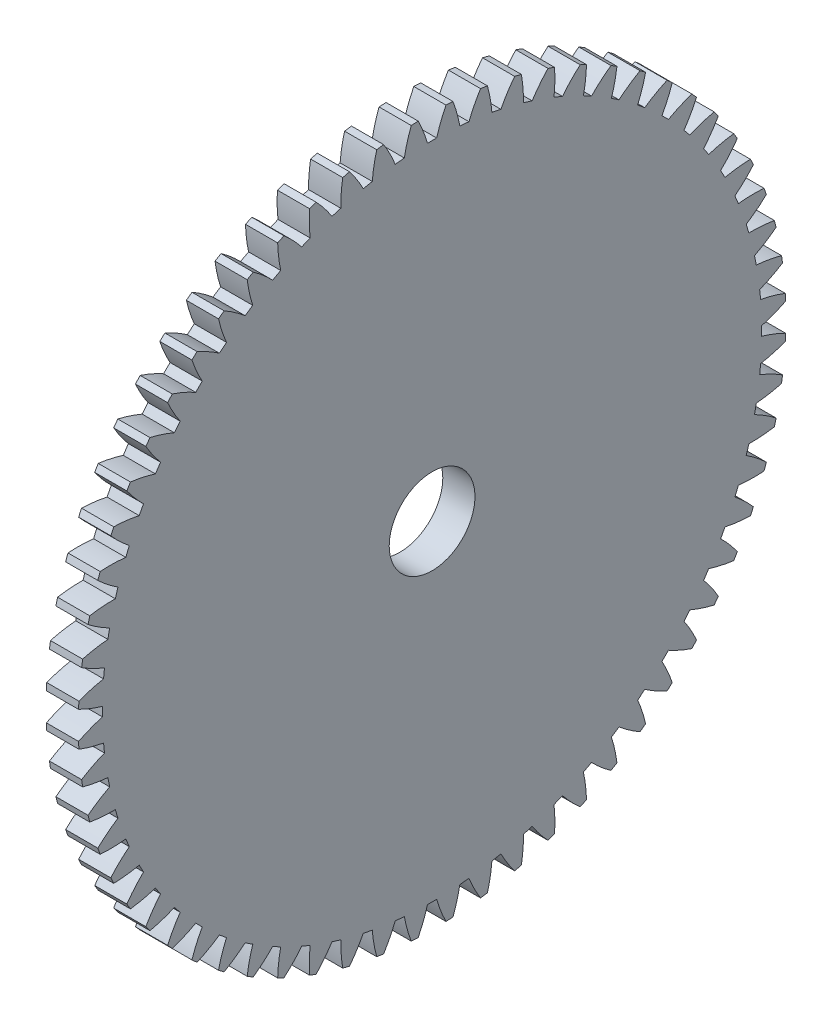
SolidWorks part; units mm, degrees
ref_plane "Plane1" through (0, 0, 0) normal (0, 0, 1) x (1, 0, 0)
ref_plane "Plane2" through (0, 0, 0) normal (0, 1, 0) x (1, 0, 0)
ref_plane "Plane3" through (0, 0, 0) normal (1, 0, 0) x (0, 0, -1)
sketch "HoldingSke" plane through (0, 0, 0) normal (0, 1, 0) x (1, 0, 0)
  line L0 (0, 0) -> (0.4384, -0.8988)
  line L1 (-15, 0) -> (100, 0) construction
  line L2 (0, 0) -> (-2.1039, 2.3779)
  line L3 (0, 0) -> (-11.863, 4.5341)
  line L4 (0, 0) -> (3.7858, 7.762)
  line L5 (0, 0) -> (-46.8476, -17.4728)
  line L6 (0, 0) -> (-2.4869, -1.6779)
  line L7 (-2.1039, 2.3779) -> (8.6586, 51.2059)
  line L8 (-76.2, 54.61) -> (-74.8, 54.61)
  line L9 (-71.009, 38.7566) -> (-53.1078, 45.2721)
  line L10 (-76.2, 71.12) -> (104.1128, 71.12)
  line L11 (0, 0) -> (-3, 0)
  line L12 (-76.2, 101.6) -> (-76.162, 101.6)
  line L13 (24.9733, 27.94) -> (52.9518, 28.4284)
  line L14 (24.9733, 27.94) -> (24.9743, 27.94)
  line L15 (24.9733, 27.94) -> (100.4006, 29.5858)
  line L16 (-63.627, -1) -> (-12.827, -1)
  circle A0 centre (0, 0) radius 4
  circle A1 centre (0, 0) radius 30.749
  circle A2 centre (0, 0) radius 37.5
  circle A3 centre (0, 0) radius 4
  dimension "MHD" = 61.498
  dimension "Hub_dia" = 75
  dimension "Bore" = 8
  dimension "MBD" = 8
  dimension "Num_teeth" = 64
  dimension "Pitch_radius" = 180.3128
  dimension "Pitch" = 1
  dimension "Width" = 3
  dimension "Overall_len" = 50
  dimension "Show_teeth" = 64
  dimension "Thickness" = 3
  dimension "OAL" = 50.0001
  dimension "T_dim" = 1.4
  dimension "Ap" = 20
  dimension "H" = 19.05
  dimension "Backlash" = 0.038
  dimension "Addendum_fac" = 1
  dimension "Dedendum_fac" = 1.25
  dimension "Clearance_fac" = 0.25
  dimension "Dedendum_add" = 0.001
  dimension "Module" = 1
sketch "BasProSke" plane through (0, 0, 0) normal (0, 1, 0) x (1, 0, 0)
  line L0 (-10, 0) -> (60, 0) construction
  line L1 (0, 0) -> (0, 33)
  line L2 (0, 0) -> (3, 0)
  line L3 (3, 0) -> (3, 33)
  line L4 (3, 33) -> (0, 33)
  dimension "Diameter" = 66
  dimension "Thickness" = 3
revolve "Base-Revolve" add sketch "BasProSke" angle 360 about L0
sketch "TooCutSke" plane through (0, 0, 0) normal (1, 0, 0) x (0, 0, -1)
  line L1 (0, 0) -> (0, 107) construction
  line L2 (0, 0) -> (-0.8518, 31.9887) construction
  line L3 (0, 0) -> (-3.1395, 63.9068) construction
  line L4 (-0.8518, 31.9887) -> (-1.5698, 31.9534) construction
  arc A0 (0.4278, 30.746) -> (-0.4278, 30.746) centre (0, 0) ccw
  arc A1 (1.3075, 32.9995) -> (-1.3075, 32.9995) centre (0, 0) ccw
  circle A2 centre (0, 0) radius 32 construction
  circle A3 centre (0, 0) radius 30.0702 construction
  arc A4 (-0.4278, 30.746) -> (-1.3075, 32.9995) centre (-12.7379, 27.2389) ccw
  arc A5 (1.3075, 32.9995) -> (0.4278, 30.746) centre (12.7379, 27.2389) ccw
  dimension "Root_dia" = 61.498
  dimension "Overcut_dia" = 66.0508
  dimension "Pitch_dia" = 64
  dimension "Base_dia" = 60.1403
  dimension "Flank_rad" = 12.8
  dimension "Half_ang" = 2.813
  dimension "Half_CT" = 0.7188
extrude "ToothCut" cut sketch "TooCutSke" along normal through all
fillet "Breaks" [suppressed] radius 0.02
fillet "RootFillets" [suppressed] radius 0.251
pattern_circular "TeethCuts" count 64 over 360 about axis through (0, 0, 0) along (1, 0, 0) of "ToothCut", "RootFillets", "Breaks"
sketch "HubNeaOneSke" plane through (0, 0, 0) normal (-1, 0, 0) x (0, 0, 1)
  circle A0 centre (0, 0) radius 30.749
  dimension "Diameter" = 61.498
extrude "HubNearOne" [suppressed] add sketch "HubNeaOneSke" along normal blind 47.0001
sketch "HubNeaBotSke" plane through (0, 0, 0) normal (-1, 0, 0) x (0, 0, 1)
  circle A0 centre (0, 0) radius 30.749
  dimension "Diameter" = 61.498
extrude "HubNearBoth" [suppressed] add sketch "HubNeaBotSke" along normal blind 23.5
ref_plane "FarPln" through (3, 0, 0) normal (1, 0, 0) x (0, 0, -1)
sketch "HubFarSke" plane through (3, 0, 0) normal (1, 0, 0) x (0, 0, -1)
  circle A0 centre (0, 0) radius 30.749
  dimension "Diameter" = 61.498
extrude "HubFar" [suppressed] add sketch "HubFarSke" along normal blind 23.5
sketch "BorSke" plane through (0, 0, 0) normal (1, 0, 0) x (0, 0, -1)
  circle A0 centre (0, 0) radius 4
  dimension "Diameter" = 8
extrude "Bore" cut sketch "BorSke" along normal mid plane 100.0001
sketch "KeySke" plane through (0, 0, 0) normal (1, 0, 0) x (0, 0, -1)
  line L0 (-1.5, 0) -> (-1.5, 5.4)
  line L1 (-1.5, 5.4) -> (1.5, 5.4)
  line L2 (1.5, 5.4) -> (1.5, 0)
  line L3 (0, 0) -> (0, 34) construction
  line L4 (-1.5, 0) -> (1.5, 0)
  dimension "Offset" = 5.4
  dimension "Width" = 3
extrude "Keyway" [suppressed] cut sketch "KeySke" along normal mid plane 100.0001
pattern_circular "Keyway2" [suppressed] count 2 every 90 about axis through (-10, 0, 0) along (1, 0, 0)
equation "' \"Module@HoldingSke\" = 6.35"
equation "' \"Num_teeth@HoldingSke\" = 12"
equation "' \"Ap@HoldingSke\" =  20"
equation "' \"Width@HoldingSke\" = 0.5 * 25.4"
equation "' \"Hub_dia@HoldingSke\"= 1 * 25.4"
equation "' \"Overall_len@HoldingSke\" = 1.0 * 25.4"
equation "' \"Bore@HoldingSke\" = 0.75 * 25.4"
equation "' \"T_dim@HoldingSke\" = 0.1 * 25.4"
equation "' \"Width@KeySke\" = 0.25 * 25.4"
equation "' \"Show_teeth@HoldingSke\" = 13"
equation "' \"Backlash@HoldingSke\" = 0.009 * 25.4"
equation "' \"Addendum_fac@HoldingSke\" = 1.0"
equation "' \"Dedendum_fac@HoldingSke\" = 1.25"
equation "' \"Dedendum_add@HoldingSke\" = 0.00005 * 25.4"
equation "' \"Clearance_fac@HoldingSke\" = 0.25"
equation "\"Pitch@HoldingSke\" = 1 / \"Module@HoldingSke\""
equation "\"Overcut_dia@TooCutSke\" = (\"Num_teeth@HoldingSke\" + 2 * \"Addendum_fac@HoldingSke\") / \"Pitch@HoldingSke\" + 0.002 * 25.4"
equation "\"Pitch_dia@TooCutSke\" = \"Num_teeth@HoldingSke\" / \"Pitch@HoldingSke\""
equation "\"Base_dia@TooCutSke\" = \"Num_teeth@HoldingSke\" / \"Pitch@HoldingSke\" * cos((\"Ap@HoldingSke\"  * 3.14159265 / 180))"
equation "\"Root_dia@TooCutSke\" = (\"Num_teeth@HoldingSke\" + 2) / \"Pitch@HoldingSke\" - 2 * (\"Addendum_fac@HoldingSke\" + \"Dedendum_fac@HoldingSke\") / \"Pitch@HoldingSke\" - \"Dedendum_add@HoldingSke\" * 2"
equation "\"Half_ang@TooCutSke\" = 180 / \"Num_teeth@HoldingSke\""
equation "\"Half_CT@TooCutSke\" = \"Num_teeth@HoldingSke\" / \"Pitch@HoldingSke\" * sin((3.14159265 / 2 / \"Num_teeth@HoldingSke\")) / 2 - 7 * \"Backlash@HoldingSke\" / 4"
equation "\"Flank_rad@TooCutSke\" = \"Num_teeth@HoldingSke\" / \"Pitch@HoldingSke\" / 5"
equation "\"Radius@RootFillets\" = \"Clearance_fac@HoldingSke\" / \"Pitch@HoldingSke\" + \"Dedendum_add@HoldingSke\""
equation "\"Break_rad@Breaks\" = 0.02 / \"Pitch@HoldingSke\""
equation "\"Thickness@HoldingSke\" = \"Width@HoldingSke\""
equation "\"OAL@HoldingSke\" = \"Thickness@HoldingSke\""
equation "\"MHD@HoldingSke\" = (\"Num_teeth@HoldingSke\" + 2) / \"Pitch@HoldingSke\" - 2 * (\"Addendum_fac@HoldingSke\" + \"Dedendum_fac@HoldingSke\")  / \"Pitch@HoldingSke\" - \"Dedendum_add@HoldingSke\" * 2"
equation "\"MBD@HoldingSke\" = (\"Num_teeth@HoldingSke\" + 2) / \"Pitch@HoldingSke\" - 2 * (\"Addendum_fac@HoldingSke\" + \"Dedendum_fac@HoldingSke\")  / \"Pitch@HoldingSke\" - \"Dedendum_add@HoldingSke\" * 2 - 0.002 * 25.4"
equation "\"MHD@HoldingSke\" = ((sgn( \"MHD@HoldingSke\" - \"Hub_dia@HoldingSke\" )-1)*( \"MHD@HoldingSke\" - \"Hub_dia@HoldingSke\" ))/-2+ \"Hub_dia@HoldingSke\""
equation "\"MBD@HoldingSke\" = ((sgn( \"MBD@HoldingSke\" - \"Bore@HoldingSke\" )-1)*( \"MBD@HoldingSke\" - \"Bore@HoldingSke\" ))/-2+ \"Bore@HoldingSke\""
equation "\"OAL@HoldingSke\" = ((sgn( \"OAL@HoldingSke\" - \"Overall_len@HoldingSke\" )+1)*( \"OAL@HoldingSke\" - \"Overall_len@HoldingSke\" ))/2 + \"Overall_len@HoldingSke\" + 0.000002 * 25.4"
equation "\"Num_teeth@TeethCuts\" = int( \"Show_teeth@HoldingSke\" ) + 1"
equation "\"Num_teeth@TeethCuts\" = ((sgn( \"Num_teeth@TeethCuts\" - \"Num_teeth@HoldingSke\" )-1)*( \"Num_teeth@TeethCuts\" - \"Num_teeth@HoldingSke\" ))/-2+ \"Num_teeth@HoldingSke\""
equation "\"Num_teeth@TeethCuts\" = ((sgn( \"Num_teeth@TeethCuts\" - 2.0)+1)*( \"Num_teeth@TeethCuts\" - 2.0))/2 +2.0"
equation "\"Angle@TeethCuts\" = 360.0 / \"Num_teeth@HoldingSke\""
equation "\"Diameter@BasProSke\" = (\"Num_teeth@HoldingSke\" + 2 * \"Addendum_fac@HoldingSke\") / \"Pitch@HoldingSke\""
equation "\"Thickness@BasProSke\"  = \"Thickness@HoldingSke\""
equation "' \"Fillet_rad@BasProSke\" =  \"Thickness@HoldingSke\" * 0.05"
equation "\"MHD@HoldingSke\" = ((sgn( \"MHD@HoldingSke\" - \"Root_dia@TooCutSke\" )-1)*( \"MHD@HoldingSke\" - \"Root_dia@TooCutSke\" ))/-2+ \"Root_dia@TooCutSke\""
equation "\"Diameter@HubNeaOneSke\" = \"MHD@HoldingSke\""
equation "\"Length@HubNearOne\" = \"OAL@HoldingSke\" - \"Thickness@BasProSke\""
equation "\"Diameter@HubNeaBotSke\" = \"MHD@HoldingSke\""
equation "\"Length@HubNearBoth\" = ( \"OAL@HoldingSke\" - \"Thickness@BasProSke\" ) / 2.0"
equation "\"Thickness@FarPln\" = \"Thickness@BasProSke\""
equation "\"Diameter@HubFarSke\" = \"MHD@HoldingSke\""
equation "\"Length@HubFar\" = ( \"OAL@HoldingSke\" - \"Thickness@BasProSke\" ) / 2.0"
equation "\"Diameter@BorSke\" = \"MBD@HoldingSke\""
equation "\"D1@Bore\" = \"OAL@HoldingSke\" * 2.0"
equation "\"D1@Keyway\" = \"OAL@HoldingSke\" * 2.0"
equation "\"Offset@KeySke\" = \"T_dim@HoldingSke\" + \"MBD@HoldingSke\" / 2.0"
